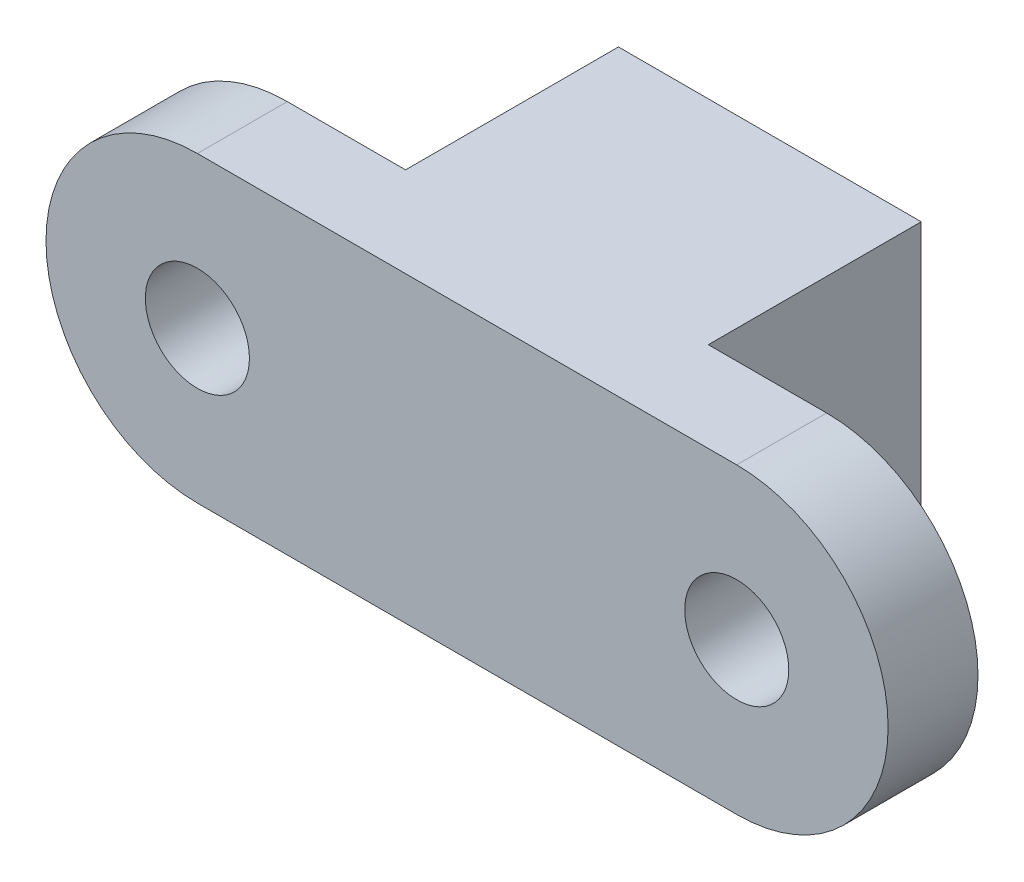
SolidWorks part; units mm, degrees
ref_plane "Front Plane" through (0, 0, 0) normal (0, 0, 1) x (1, 0, 0)
ref_plane "Top Plane" through (0, 0, 0) normal (0, 1, 0) x (1, 0, 0)
ref_plane "Right Plane" through (0, 0, 0) normal (1, 0, 0) x (0, 0, -1)
sketch "Sketch1" plane through (0, 0, 0) normal (0, 0, 1) x (1, 0, 0)
  line L0 (0, 0) -> (114, 0) construction
  line L1 (0, 32) -> (114, 32)
  line L2 (0, -32) -> (114, -32)
  arc A0 (0, 32) -> (0, -32) centre (0, 0) ccw
  arc A1 (114, -32) -> (114, 32) centre (114, 0) ccw
  circle A2 centre (0, 0) radius 11
  circle A3 centre (114, 0) radius 11
  point P3 (57, 0)
  point P12 (57, 0)
  dimension "D2" = 22
  dimension "D3" = 32
  dimension "D4" = 22
  dimension "D1" = 114
extrude "Boss-Extrude1" add sketch "Sketch1" along normal blind 19
sketch "Sketch2" plane through (0, 0, 0) normal (0, 0, -1) x (-1, 0, 0)
  line L0 (-57, 32) -> (-57, -32) construction
  line L1 (-114, 32) -> (0, 32) construction
  line L2 (0, -32) -> (-114, -32) construction
  line L3 (-89, 32) -> (-89, -32)
  line L4 (-25, 32) -> (-25, -32)
  line L5 (-89, 32) -> (-25, 32)
  line L6 (-25, -32) -> (-89, -32)
  dimension "D1" = 32
extrude "Boss-Extrude2" add sketch "Sketch2" along normal blind 45
sketch "Sketch15" plane through (89, 0, 0) normal (1, 0, 0) x (0, 0, -1)
  line L0 (45, -32) -> (45, 19)
  line L1 (45, 32) -> (45, -32) construction
  line L2 (45, 19) -> (-6, -32)
  line L3 (-19, -32) -> (0, -32) construction
  line L4 (-6, -32) -> (45, -32)
  dimension "D1" = 13
  dimension "D2" = 13
extrude "Cut-Extrude8" cut sketch "Sketch15" against normal blind 38 from offset 13
